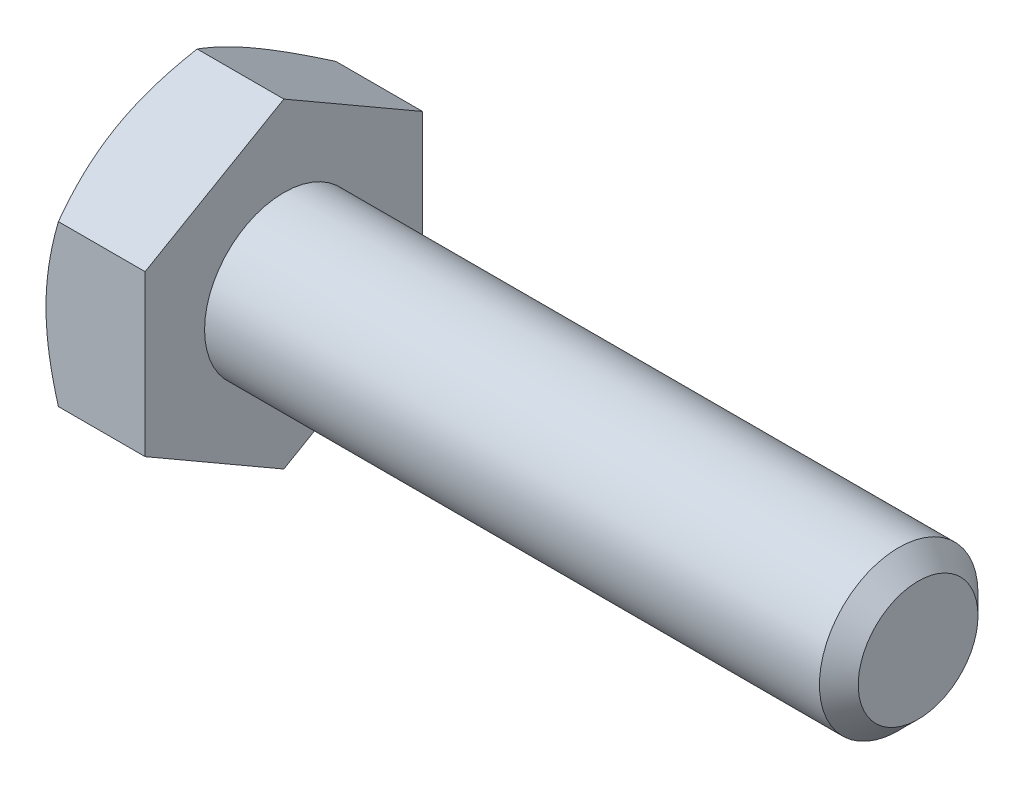
SolidWorks part; units mm, degrees
material "Alloy Steel"
ref_plane "Front Plane" through (0, 0, 0) normal (0, 0, 1) x (1, 0, 0)
ref_plane "Top Plane" through (0, 0, 0) normal (0, 1, 0) x (1, 0, 0)
ref_plane "Right Plane" through (0, 0, 0) normal (1, 0, 0) x (0, 0, -1)
sketch "Sketch1" plane through (0, 0, 0) normal (0, 0, 1) x (1, 0, 0)
  line L0 (-14.6844, 0) -> (14.6844, 0) construction
  line L1 (14.6844, 3.175) -> (14.6844, -3.175) construction
  line L2 (-10.7156, 5.5562) -> (-10.7156, -5.5562) construction
  line L3 (-14.6844, 5.5562) -> (-14.6844, -5.5562) construction
  point P9 (-10.7156, 0)
  point P10 (10.2394, -3.175)
  dimension "D1" = 4.445
  dimension "Screw Dia" = 6.35
  dimension "Hex" = 11.1125
  dimension "Head Ht" = 3.9688
  dimension "Screw Lenght" = 25.4
ref_plane "Plane2" through (14.6844, 0, 0) normal (1, 0, 0) x (0, 0, -1)
sketch "Sketch5" plane through (14.6844, 0, 0) normal (1, 0, 0) x (0, 0, -1)
  circle A0 centre (0, 0) radius 3.175
extrude "Boss-Extrude3" add sketch "Sketch5" against normal up to vertex (25.4 mm away) up to point (-10.7156, 0, 0)
sketch "Sketch9" plane through (14.6844, 0, 0) normal (1, 0, 0) x (0, 0, -1)
  circle A1 centre (0, 0) radius 3.175
  circle A2 centre (0, 0) radius 3.175
  dimension "D1" = 0
curve "Helix/Spiral1" pitch 1.27 height 26.67 turns 21 parameters "Pitch"=1.27
chamfer "Chamfer1" distance 0.7772 angle 45 1 edges at (14.6844, 0, -3.175)
sketch "Sketch10" plane through (0, 0, 0) normal (0, 0, 1) x (1, 0, 0)
  line L0 (14.6844, 3.175) -> (15.1606, 2.3501)
  line L1 (15.1606, 2.3501) -> (15.3194, 2.3501)
  line L2 (15.3194, 2.3501) -> (15.7956, 3.175)
  line L3 (14.6844, 3.175) -> (15.7956, 3.175)
  line L4 (15.24, 3.175) -> (15.24, 2.3501) construction
  line L5 (14.9225, 2.7626) -> (15.5575, 2.7626) construction
  dimension "D1" = 60
  dimension "D2" = 0.1588
  dimension "D3" = 0.635
sketch "Sketch6" plane through (-10.7156, 0, 0) normal (-1, 0, 0) x (0, 0, 1)
  line L0 (0, 5.5562) -> (0, -5.5562) construction
  line L1 (5.5563, 3.2079) -> (0, 6.4158)
  line L2 (0, 6.4158) -> (-5.5562, 3.2079)
  line L3 (-5.5562, 3.2079) -> (-5.5562, -3.2079)
  line L4 (-5.5562, -3.2079) -> (0, -6.4158)
  line L5 (0, -6.4158) -> (5.5563, -3.2079)
  line L6 (5.5563, -3.2079) -> (5.5563, 3.2079)
  circle A0 centre (0, 0) radius 5.5563 construction
extrude "Boss-Extrude4" add sketch "Sketch6" along normal up to vertex (3.9688 mm away) up to point (-14.6844, -5.5562, 0)
sketch "Sketch7" plane through (-14.6844, 0, 0) normal (-1, 0, 0) x (0, 0, 1)
  circle A0 centre (0, 0) radius 5.5563 construction
  circle A1 centre (0, 0) radius 5.5563
sketch "Sketch8" plane through (-14.6844, 0, 0) normal (-1, 0, 0) x (0, 0, 1)
  circle A0 centre (0, 0) radius 5.5563 construction
  circle A1 centre (0, 0) radius 5.5563
extrude "Cut-Extrude3" cut sketch "Sketch8" against normal through all draft 60 flip side to cut
sketch "Sketch12" plane through (-14.6844, 0, 0) normal (-1, 0, 0) x (0, 0, 1)
  line L0 (0, 4.2783) -> (0, 2.3892) construction
  line L1 (0.1667, 4.2783) -> (0.1667, 2.3892)
  line L2 (-0.1667, 4.2783) -> (-0.1667, 2.3892)
  line L3 (0, 3.175) -> (0, -3.175) construction
  arc A0 (0.1667, 4.2783) -> (-0.1667, 4.2783) centre (0, 4.2783) ccw
  arc A1 (-0.1667, 2.3892) -> (0.1667, 2.3892) centre (0, 2.3892) ccw
  circle A3 centre (0, 0) radius 2.2225 construction
  circle A4 centre (0, 0) radius 4.445 construction
  point P2 (0, 3.3337)
  dimension "D1" = 4.445
  dimension "D3" = 8.89
  dimension "D2" = 0.3334
extrude "Cut-Extrude4" cut sketch "Sketch12" against normal blind 0.254
pattern_circular "CirPattern1" count 3 over 360 about axis through (0, 0, 0) along (1, 0, 0) of "Cut-Extrude4"
equation "\"D2@Sketch10\" = \"Pitch@Helix/Spiral1\"*.125"
equation "\"D3@Sketch10\" = \"Pitch@Helix/Spiral1\"*.5"
equation "\"D1@Chamfer1\" = \"Pitch@Helix/Spiral1\"*.612"
equation "\"D1@Sketch12\" = \"Hex@Sketch1\"*.4"
equation "\"D3@Sketch12\" = \"Hex@Sketch1\"*.8"
equation "\"D2@Sketch12\" = \"Hex@Sketch1\"*.03"
equation "\"D1@Sketch1\" = \"Pitch@Helix/Spiral1\"*3.5"
equation "\"D3@Helix/Spiral1\" = \"Screw Lenght@Sketch1\"+\"Pitch@Helix/Spiral1\""
